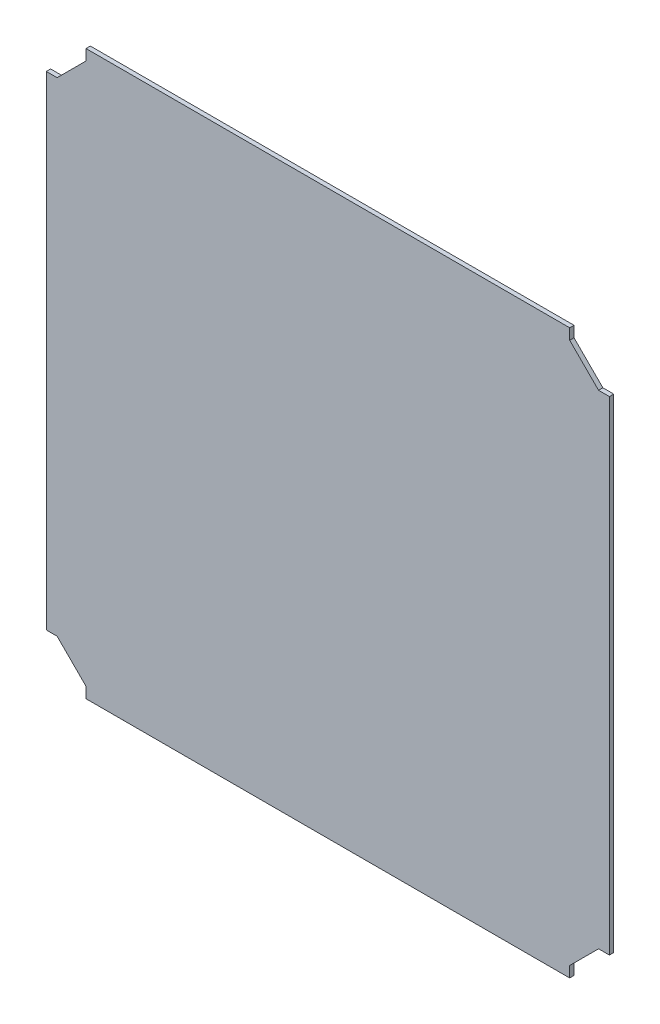
SolidWorks part; units mm, degrees
ref_plane "Alzado" through (0, 0, 0) normal (0, 0, 1) x (1, 0, 0)
ref_plane "Planta" through (0, 0, 0) normal (0, 1, 0) x (1, 0, 0)
ref_plane "Vista lateral" through (0, 0, 0) normal (1, 0, 0) x (0, 0, -1)
sketch "Sketch1" plane through (0, 0, 0) normal (0, 0, 1) x (1, 0, 0)
  line L1 (390, -390) -> (-390, -390)
  line L2 (390, -390) -> (390, 390)
  line L3 (390, 390) -> (-390, 390)
  line L4 (-390, -390) -> (-390, 390)
  line L5 (390, -390) -> (-390, 390) construction
  line L6 (390, 390) -> (-390, -390) construction
  point P0 (0, 0)
  dimension "D1" = 780
  dimension "D2" = 780
extrude "Boss-Extrude1" add sketch "Sketch1" along normal blind 6
sketch "Sketch2" plane through (0, 0, 6) normal (0, 0, 1) x (1, 0, 0)
  line L1 (-390, 390) -> (-335, 390)
  line L2 (-390, 390) -> (-390, 335)
  line L3 (-390, 335) -> (-335, 335)
  line L4 (-335, 390) -> (-335, 335)
  line L5 (390, 390) -> (335, 390)
  line L6 (390, 390) -> (390, 335)
  line L7 (390, 335) -> (335, 335)
  line L8 (335, 390) -> (335, 335)
  line L9 (390, -390) -> (335, -390)
  line L10 (390, -390) -> (390, -335)
  line L11 (390, -335) -> (335, -335)
  line L12 (335, -390) -> (335, -335)
  line L13 (-390, -390) -> (-335, -390)
  line L14 (-390, -390) -> (-390, -335)
  line L15 (-390, -335) -> (-335, -335)
  line L16 (-335, -390) -> (-335, -335)
  dimension "D1" = 55
  dimension "D2" = 55
extrude "Cut-Extrude1" cut sketch "Sketch2" against normal blind 6
chamfer "Chamfer1" distance 40 angle 45 4 edges at (335, 335, 3) (335, -335, 3) (-335, -335, 3) (-335, 335, 3)
